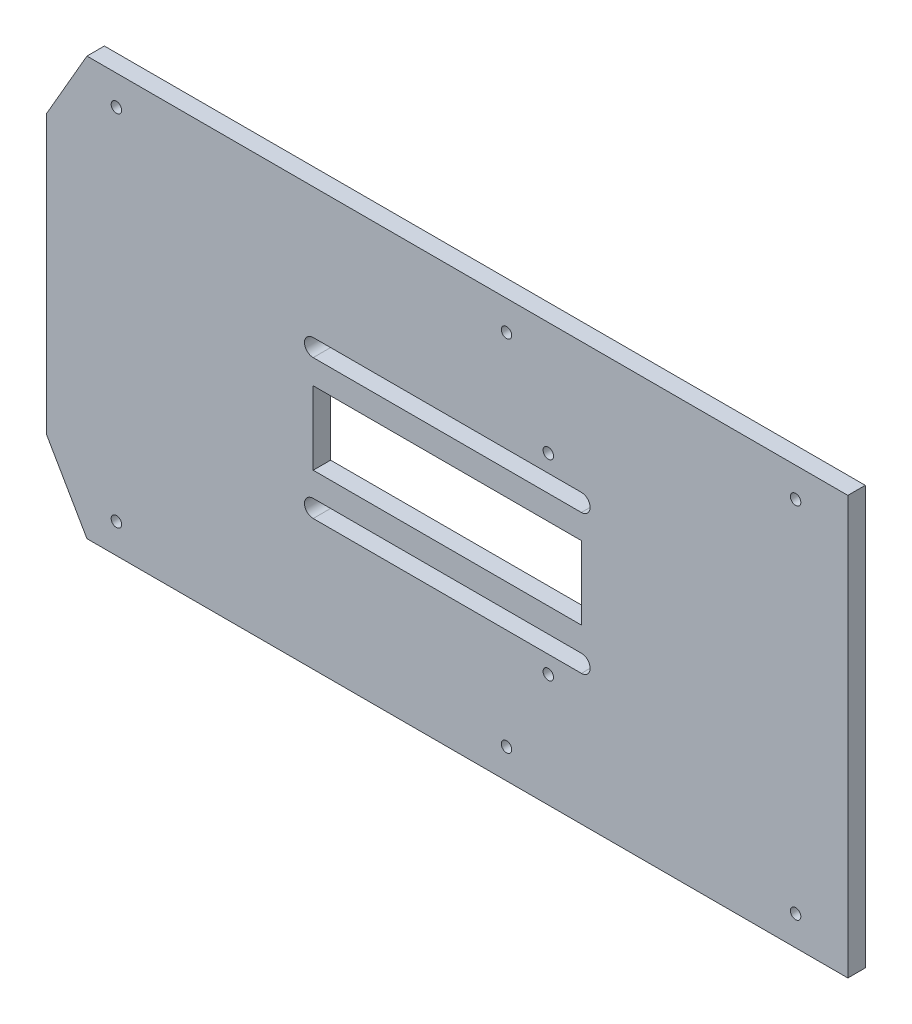
SolidWorks part; units mm, degrees
ref_plane "Plan de face" through (0, 0, 0) normal (0, 0, 1) x (1, 0, 0)
ref_plane "Plan de dessus" through (0, 0, 0) normal (0, 1, 0) x (1, 0, 0)
ref_plane "Plan de droite" through (0, 0, 0) normal (1, 0, 0) x (0, 0, -1)
sketch "Esquisse1" plane through (0, 0, 0) normal (0, 0, 1) x (1, 0, 0)
  line L0 (-115, 0) -> (115, 0)
  line L1 (115, 0) -> (115, 60)
  line L2 (115, 60) -> (-103.453, 60)
  line L3 (-103.453, 60) -> (-115, 40)
  line L4 (-115, 40) -> (-115, 0)
  point P2 (0, 0)
  dimension "D1" = 230
  dimension "D2" = 60
  dimension "D3" = 40
  dimension "D4" = 120
extrude "Boss.-Extru.1" add sketch "Esquisse1" along normal blind 5
mirror "Symétrie1" of "Boss.-Extru.1"
sketch "Esquisse2" plane through (0, 0, 5) normal (0, 0, 1) x (1, 0, 0)
  line L1 (-38.5, -10.5) -> (38.5, -10.5)
  line L2 (-38.5, -10.5) -> (-38.5, 10.5)
  line L3 (-38.5, 10.5) -> (38.5, 10.5)
  line L4 (38.5, -10.5) -> (38.5, 10.5)
  line L5 (-38.5, -10.5) -> (38.5, 10.5) construction
  line L6 (-38.5, 10.5) -> (38.5, -10.5) construction
  point P0 (0, 0)
  dimension "D1" = 77
  dimension "D2" = 21
extrude "Enlèv. mat.-Extru.1" cut sketch "Esquisse2" against normal up to next
sketch "Esquisse3" plane through (0, 0, 5) normal (0, 0, 1) x (1, 0, 0)
  line L0 (-38.5, 20) -> (38.5, 20) construction
  line L1 (-38.5, 22.5) -> (38.5, 22.5)
  line L2 (-38.5, 17.5) -> (38.5, 17.5)
  line L3 (38.5, 10.5) -> (-38.5, 10.5) construction
  line L4 (115, 60) -> (-103.453, 60) construction
  arc A0 (-38.5, 22.5) -> (-38.5, 17.5) centre (-38.5, 20) ccw
  arc A1 (38.5, 17.5) -> (38.5, 22.5) centre (38.5, 20) ccw
  point P2 (0, 20)
  point P7 (0, 0)
  point P8 (26.3686, 19.8797)
  dimension "D1" = 5
  dimension "D2" = 40
extrude "Enlèv. mat.-Extru.2" cut sketch "Esquisse3" against normal up to next
sketch "Esquisse4" plane through (0, 0, 0) normal (0, 0, -1) x (-1, 0, 0)
  circle A0 centre (-100, 51.5) radius 1.5
  circle A1 centre (-17, 51.5) radius 1.5
  circle A2 centre (95, 51.5) radius 1.5
  circle A3 centre (-29, 27.5) radius 1.5
  dimension "D1" = 3
extrude "Enlèv. mat.-Extru.3" cut sketch "Esquisse4" against normal up to surface (5 mm away) up to face at (0, 20, 5)
mirror "Symétrie2" about plane through (0, 0, 0) normal (0, 1, 0) of "Enlèv. mat.-Extru.3"
mirror "Symétrie3" about plane through (0, 0, 0) normal (0, 1, 0) of "Enlèv. mat.-Extru.2"
